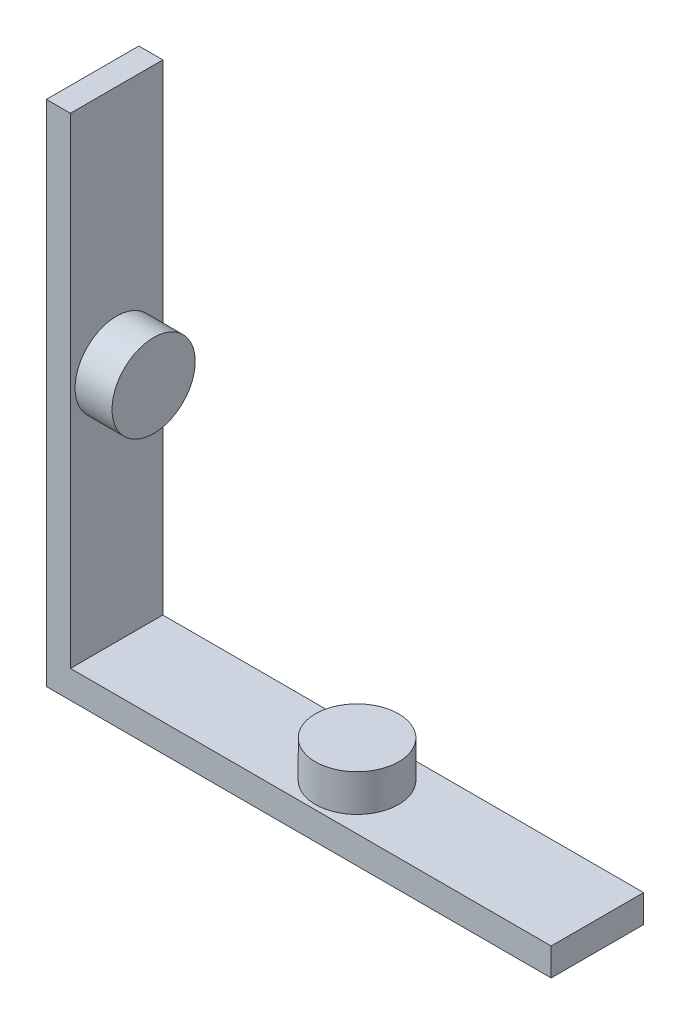
SolidWorks part; units mm, degrees
ref_plane "Front Plane" through (0, 0, 0) normal (0, 0, 1) x (1, 0, 0)
ref_plane "Top Plane" through (0, 0, 0) normal (0, 1, 0) x (1, 0, 0)
ref_plane "Right Plane" through (0, 0, 0) normal (1, 0, 0) x (0, 0, -1)
sketch "Sketch1" plane through (0, 0, 0) normal (0, 0, 1) x (1, 0, 0)
  line L0 (0, 275) -> (0, 0)
  line L1 (0, 0) -> (275, 0)
  line L2 (275, 0) -> (275, 15)
  line L3 (275, 15) -> (15, 15)
  line L4 (15, 15) -> (15, 275)
  line L5 (15, 275) -> (0, 275)
  dimension "D1" = 275
  dimension "D2" = 15
extrude "Boss-Extrude1" add sketch "Sketch1" along normal blind 50
sketch "Sketch2" plane through (0, 15, 0) normal (0, 1, 0) x (1, 0, 0)
  line L0 (15, -25) -> (275, -25) construction
  line L1 (15, -50) -> (15, 0) construction
  line L2 (275, -50) -> (275, 0) construction
  circle A1 centre (145, -25) radius 22.5
  dimension "D1" = 45
extrude "Boss-Extrude2" add sketch "Sketch2" along normal blind 20
sketch "Sketch3" plane through (15, 0, 0) normal (1, 0, 0) x (0, 0, -1)
  line L0 (-25, 15) -> (-25, 275) construction
  line L1 (-50, 15) -> (0, 15) construction
  line L2 (-50, 275) -> (0, 275) construction
  circle A0 centre (-25, 145) radius 22.5
  dimension "D1" = 45
extrude "Boss-Extrude3" add sketch "Sketch3" along normal blind 20
chamfer "Chamfer2" distance 2 angle 45 4 edges at (0, 0, 25) (0, 137.5, 0) (0, 275, 25) (0, 137.5, 50)
